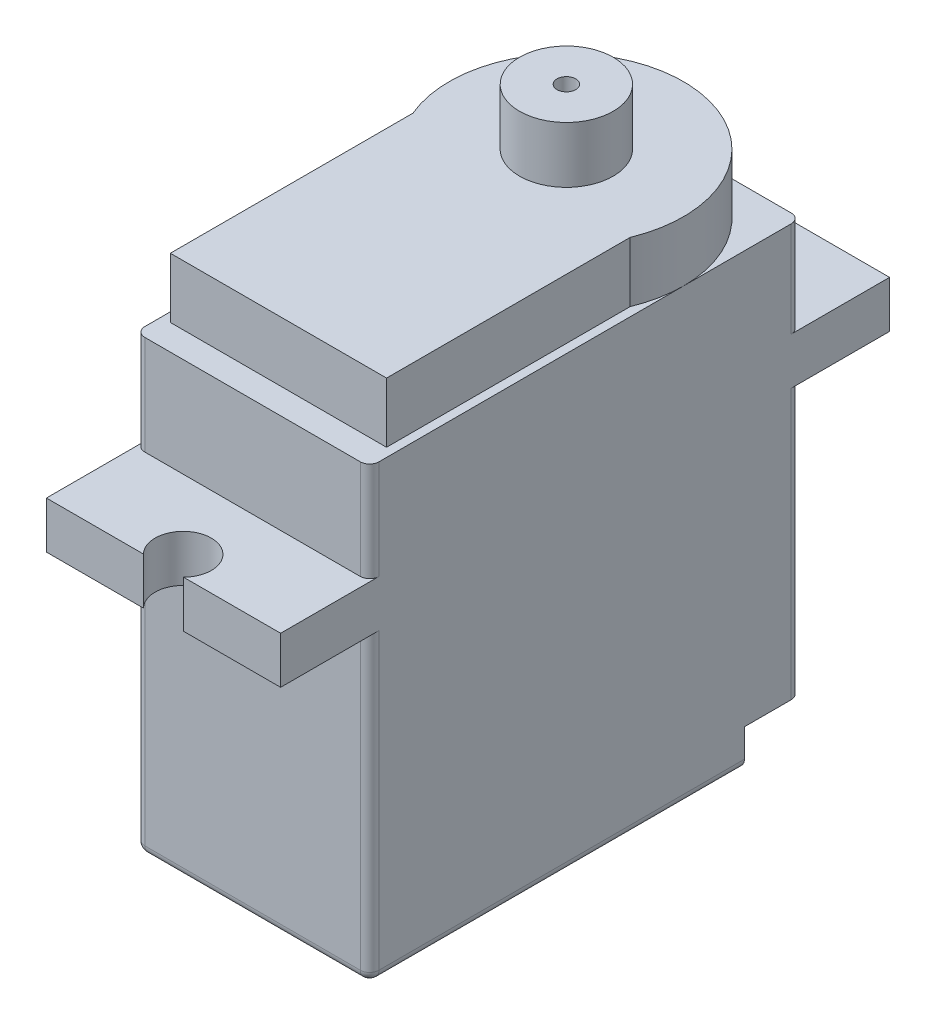
SolidWorks part; units mm, degrees
ref_plane "Front Plane" through (0, 0, 0) normal (0, 0, 1) x (1, 0, 0)
ref_plane "Top Plane" through (0, 0, 0) normal (0, 1, 0) x (1, 0, 0)
ref_plane "Right Plane" through (0, 0, 0) normal (1, 0, 0) x (0, 0, -1)
sketch "Sketch1" plane through (0, 0, 0) normal (0, 1, 0) x (1, 0, 0)
  line L0 (-6.25, 11.5) -> (6.25, -11.5) construction
  line L1 (-6.25, 11.5) -> (6.25, 11.5)
  line L2 (-6.25, 11.5) -> (-6.25, -11.5)
  line L3 (-6.25, -11.5) -> (6.25, -11.5)
  line L4 (6.25, 11.5) -> (6.25, -11.5)
  line L5 (6.25, 11.5) -> (-6.25, -11.5) construction
  point P7 (0, 0)
  dimension "D1" = 23
  dimension "D2" = 12.5
extrude "Boss-Extrude1" add sketch "Sketch1" along normal blind 24
sketch "Sketch2" plane through (0, 24, 0) normal (0, 1, 0) x (1, 0, 0)
  line L0 (6.25, -11.5) -> (6.25, 11.5) construction
  line L1 (6.25, 11.5) -> (-6.25, 11.5) construction
  line L2 (-6.25, 11.5) -> (-6.25, -11.5) construction
  line L3 (6.25, -11.5) -> (6.25, 11.5) construction
  line L4 (6.25, 11.5) -> (-6.25, 11.5) construction
  line L5 (-6.25, 11.5) -> (-6.25, -11.5) construction
  line L8 (-5.7576, 2.8185) -> (-5.7576, -10.1288)
  line L9 (-5.7576, -10.1288) -> (5.7817, -10.1288)
  line L10 (5.7817, 2.8763) -> (5.7817, -10.1288)
  arc A0 (5.7817, 2.8763) -> (-5.7576, 2.8185) centre (0, 5.25) ccw
extrude "Boss-Extrude2" add sketch "Sketch2" along normal blind 3.2 contours A0 L8 L9 L10
sketch "Sketch3" plane through (0, 27.2, 0) normal (0, 1, 0) x (1, 0, 0)
  arc A0 (5.7817, 2.8763) -> (-5.7576, 2.8185) centre (0, 5.25) ccw construction
  arc A1 (5.7817, 2.8763) -> (-5.7576, 2.8185) centre (0, 5.25) ccw construction
  circle A2 centre (0, 5.25) radius 2.5
  circle A3 centre (0, 5.25) radius 0.5
  dimension "D1" = 5
  dimension "D2" = 1
extrude "Boss-Extrude3" add sketch "Sketch3" along normal blind 3
sketch "Sketch4" plane through (0, 0, -11.5) normal (0, 0, -1) x (-1, 0, 0)
  line L0 (6.25, 24) -> (6.25, 0) construction
  line L1 (-6.25, 24) -> (-6.25, 0) construction
  line L2 (6.25, 24) -> (6.25, 0) construction
  line L3 (-6.25, 24) -> (-6.25, 0) construction
  line L5 (-6.25, 18.9) -> (6.25, 18.9)
  line L6 (-6.25, 18.9) -> (-6.25, 16.4)
  line L7 (-6.25, 16.4) -> (6.25, 16.4)
  line L8 (6.25, 18.9) -> (6.25, 16.4)
  dimension "D1" = 16.4
  dimension "D2" = 2.5
extrude "Boss-Extrude4" add sketch "Sketch4" along normal blind 4.75
sketch "Sketch5" plane through (0, 0, 11.5) normal (0, 0, 1) x (1, 0, 0)
  line L0 (-6.25, 24) -> (-6.25, 0) construction
  line L1 (6.25, 24) -> (6.25, 0) construction
  line L2 (-6.25, 24) -> (-6.25, 0) construction
  line L3 (6.25, 24) -> (6.25, 0) construction
  line L5 (6.25, 16.2) -> (-6.25, 16.2)
  line L6 (6.25, 16.2) -> (6.25, 18.7)
  line L7 (6.25, 18.7) -> (-6.25, 18.7)
  line L8 (-6.25, 16.2) -> (-6.25, 18.7)
  dimension "D1" = 16.2
  dimension "D2" = 2.5
extrude "Boss-Extrude5" add sketch "Sketch5" along normal blind 4.75
sketch "Sketch6" plane through (0, 18.7, 0) normal (0, 1, 0) x (1, 0, 0)
  line L0 (0, -16.25) -> (0, -11.5) construction
  line L10 (6.25, -11.5) -> (-6.25, -11.5) construction
  line L11 (6.25, -16.25) -> (6.25, -11.5) construction
  line L12 (-6.25, -16.25) -> (-6.25, -11.5) construction
  line L13 (6.25, -16.25) -> (-6.25, -16.25) construction
  line L14 (6.25, -11.5) -> (-6.25, -11.5) construction
  line L15 (6.25, -16.25) -> (6.25, -11.5) construction
  line L16 (-6.25, -16.25) -> (-6.25, -11.5) construction
  line L17 (6.25, -16.25) -> (-6.25, -16.25) construction
  circle A0 centre (0, -15.2) radius 1.5
  dimension "D1" = 3
  dimension "D2" = 3.7
extrude "Cut-Extrude1" cut sketch "Sketch6" against normal up to next
sketch "Sketch8" plane through (0, 18.9, 0) normal (0, 1, 0) x (1, 0, 0)
  line L0 (-6.25, 16.25) -> (6.25, 16.25) construction
  line L1 (-6.25, 16.25) -> (-6.25, 11.5) construction
  line L2 (-6.25, 11.5) -> (6.25, 11.5) construction
  line L3 (6.25, 16.25) -> (6.25, 11.5) construction
  line L4 (-6.25, 16.25) -> (6.25, 16.25) construction
  line L5 (-6.25, 16.25) -> (-6.25, 11.5) construction
  line L6 (-6.25, 11.5) -> (6.25, 11.5) construction
  line L7 (6.25, 16.25) -> (6.25, 11.5) construction
  line L8 (0, 16.25) -> (0, 11.5) construction
  circle A0 centre (0, 15.2) radius 1.5
  dimension "D1" = 3
  dimension "D2" = 3.7
extrude "Cut-Extrude2" cut sketch "Sketch8" against normal up to next contours A0
sketch "Sketch9" plane through (6.25, 0, 0) normal (1, 0, 0) x (0, 0, -1)
  line L0 (11.5, 2) -> (8.5, 0)
  line L1 (11.5, 16.4) -> (11.5, 0) construction
  line L2 (-11.5, 0) -> (11.5, 0) construction
  line L3 (8.5, 0) -> (11.5, 0)
  line L4 (11.5, 0) -> (11.5, 2)
  line L5 (11.5, 2) -> (8.5, 2) construction
  line L6 (8.5, 2) -> (8.5, 0) construction
  dimension "D1" = 2
  dimension "3" = 3
extrude "Cut-Extrude4" cut sketch "Sketch9" against normal through all contours L0 L3 L4
sketch "Sketch10" plane through (6.25, 0, 0) normal (1, 0, 0) x (0, 0, -1)
  line L0 (11.5, 2) -> (8.5, 2)
  line L1 (8.5, 0) -> (8.5, 2)
  dimension "D1" = 3
extrude "Cut-Extrude6" cut sketch "Sketch10" against normal blind 2.3 and the other way through all flip side to cut
sketch "Sketch11" plane through (-6.25, 0, 0) normal (-1, 0, 0) x (0, 0, 1)
  line L0 (-11.5, 2) -> (-8.5, 2)
  line L1 (-8.5, 2) -> (-8.5, 0)
extrude "Cut-Extrude7" cut sketch "Sketch11" against normal blind 2.3 and the other way through all flip side to cut
fillet "Fillet1" radius 0.5 11 edges at (-6.25, 21.45, -11.5) (6.25, 21.45, -11.5) (-6.25, 21.35, 11.5) (0, 0, 11.5) (6.25, 0, 1.5) (-6.25, 0, 1.5) (6.25, 9.2, -11.5) (-6.25, 9.2, -11.5) (-6.25, 8.1, 11.5) (6.25, 8.1, 11.5) (6.25, 21.35, 11.5)
